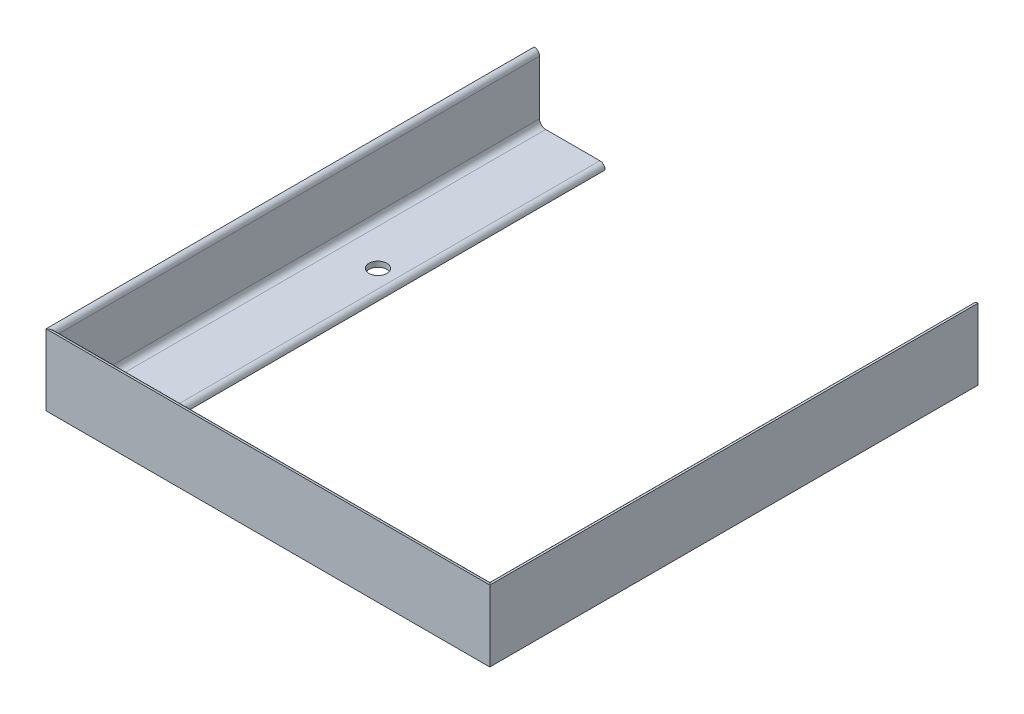
SolidWorks part; units mm, degrees
ref_plane "Front Plane" through (0, 0, 0) normal (0, 0, 1) x (1, 0, 0)
ref_plane "Top Plane" through (0, 0, 0) normal (0, 1, 0) x (1, 0, 0)
ref_plane "Right Plane" through (0, 0, 0) normal (1, 0, 0) x (0, 0, -1)
sketch3d "3DSketch1"
  line L1 (125, 0, 137.5) -> (125, 0, -137.5)
  line L2 (125, 0, 137.5) -> (-125, 0, 137.5)
  line L3 (-125, 0, 137.5) -> (-125, 0, -137.5)
  line L4 (125, 0, -137.5) -> (-125, 0, -137.5)
  line L5 (125, 0, 137.5) -> (-125, 0, -137.5) construction
  line L6 (-125, 0, 137.5) -> (125, 0, -137.5) construction
  point P0 (0, 0, 0)
  dimension "D1" = 275
  dimension "D2" = 250
other "Iron V40X40X3(1)"
ref_plane "Plane1" through (-125, 0, 137.5) normal (0, 0, -1) x (0, 1, 0)
sketch "Sketch11" plane through (-125, 0, 137.5) normal (0, 0, -1) x (0, 1, 0)
  line L0 (0, 0) -> (0, 40)
  line L1 (0, 20) -> (3, 20) construction
  line L2 (3, 37) -> (3, 6.5)
  line L3 (6.5, 3) -> (37, 3)
  line L4 (20, 3) -> (20, 0) construction
  line L5 (40, 0) -> (0, 0)
  arc A0 (40, 0) -> (37, 3) centre (37, 0) ccw
  arc A1 (0, 40) -> (3, 37) centre (0, 37) cw
  arc A2 (6.5, 3) -> (3, 6.5) centre (6.5, 6.5) cw
  point P10 (20, 0)
  point P14 (0, 20)
  point P15 (3, 20)
  point P16 (20, 3)
  point P17 (3, 40)
  point P18 (40, 3)
  point P21 (0, 0)
  dimension "D2" = 3
  dimension "D3" = 40
  dimension "Radius_1" = 3.5
  dimension "D1" = 3
sketch "Sketch12" plane through (0, 0, 0) normal (0, -1, 0) x (1, 0, 0)
  line L0 (-125, 137.5) -> (125, 137.5) construction
  circle A0 centre (-98, 117.5) radius 5
  circle A1 centre (98, 117.5) radius 5
  circle A2 centre (98, -22.5) radius 5
  circle A3 centre (-98, -22.5) radius 5
  dimension "D1" = 10
  dimension "D2" = 20
  dimension "D3" = 98
  dimension "D4" = 2
  dimension "D5" = 2
extrude "Cut-Extrude1" cut sketch "Sketch12" against normal blind 20 from offset 10
